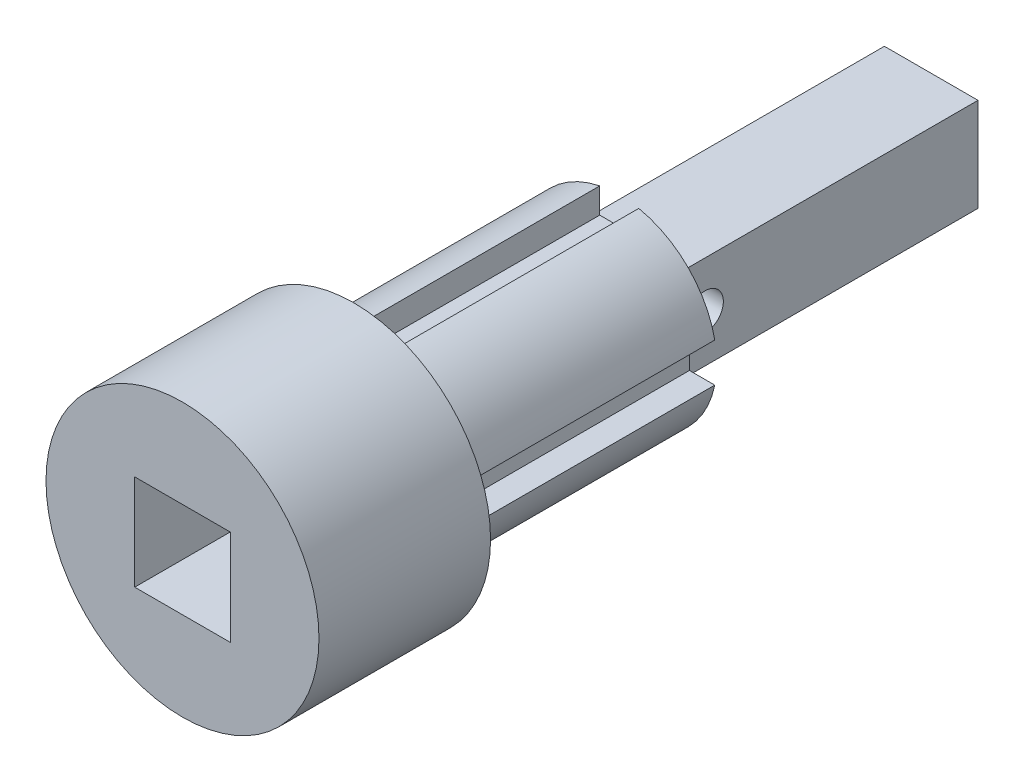
SolidWorks part; units mm, degrees
ref_plane "Plano frontal" through (0, 0, 0) normal (0, 0, 1) x (1, 0, 0)
ref_plane "Plano superior" through (0, 0, 0) normal (0, 1, 0) x (1, 0, 0)
ref_plane "Plano direito" through (0, 0, 0) normal (1, 0, 0) x (0, 0, -1)
sketch "Esboço1" plane through (0, 0, 0) normal (0, 0, 1) x (1, 0, 0)
  circle A0 centre (0, 0) radius 17.5
  dimension "D1" = 35
extrude "Ressalto-extrusão1" add sketch "Esboço1" along normal blind 22
sketch "Esboço2" plane through (0, 0, 0) normal (0, 0, -1) x (-1, 0, 0)
  line L3 (-6.125, 6.125) -> (6.125, 6.125)
  line L4 (-6.125, 6.125) -> (-6.125, -6.125)
  line L5 (-6.125, -6.125) -> (6.125, -6.125)
  line L6 (6.125, 6.125) -> (6.125, -6.125)
  point P5 (0, 0)
  dimension "D1" = 12.25
  dimension "D2" = 12.25
extrude "Corte-extrusão1" cut sketch "Esboço2" against normal blind 25
sketch "Esboço3" plane through (0, 0, 0) normal (0, 0, -1) x (-1, 0, 0)
  circle A0 centre (0, 0) radius 12.5
  dimension "D1" = 25
extrude "Ressalto-extrusão2" add sketch "Esboço3" along normal blind 34
sketch "Esboço4" plane through (0, 0, -34) normal (0, 0, -1) x (-1, 0, 0)
  line L2 (-2.5, -9) -> (2.5, -9)
  line L3 (-2.5, 15) -> (2.5, 15)
  line L4 (-2.5, 15) -> (-2.5, 9)
  line L5 (-2.5, 9) -> (2.5, 9)
  line L6 (2.5, 15) -> (2.5, 9)
  line L7 (9, 2.5) -> (15, 2.5)
  line L8 (9, 2.5) -> (9, -2.5)
  line L9 (9, -2.5) -> (15, -2.5)
  line L10 (15, 2.5) -> (15, -2.5)
  line L11 (-2.5, -15) -> (2.5, -15)
  line L12 (2.5, -15) -> (2.5, -9)
  line L13 (-2.5, -15) -> (-2.5, -9)
  line L14 (-15, 2.5) -> (-15, -2.5)
  line L15 (-9, -2.5) -> (-15, -2.5)
  line L16 (-9, 2.5) -> (-9, -2.5)
  line L17 (-9, 2.5) -> (-15, 2.5)
  dimension "D1" = 5
  dimension "D2" = 5
  dimension "D3" = 6
  dimension "D6" = 6
extrude "Corte-extrusão2" cut sketch "Esboço4" against normal blind 32
fillet "Filete2" radius 2 3 edges at (10.6237, 2.5, -2) (10.6237, -2.5, -2) (9, 0, -2)
fillet "Filete3" radius 2 3 edges at (-2.5, -10.6237, -2) (2.5, -10.6237, -2) (0, -9, -2)
fillet "Filete4" radius 2 3 edges at (-10.6237, 2.5, -2) (-9, 0, -2) (-10.6237, -2.5, -2)
fillet "Filete5" radius 2 3 edges at (-2.5, 10.6237, -2) (2.5, 10.6237, -2) (0, 9, -2)
sketch "Esboço5" plane through (0, 0, -34) normal (0, 0, -1) x (-1, 0, 0)
  line L1 (6, 6) -> (-6, 6)
  line L2 (6, 6) -> (6, -6)
  line L3 (6, -6) -> (-6, -6)
  line L4 (-6, 6) -> (-6, -6)
  line L5 (6, 6) -> (-6, -6) construction
  line L6 (6, -6) -> (-6, 6) construction
  point P0 (0, 0)
  dimension "D1" = 12
  dimension "D2" = 12
extrude "Ressalto-extrusão3" add sketch "Esboço5" along normal blind 40
sketch "Esboço6" plane through (6, 0, 0) normal (1, 0, 0) x (0, 0, -1)
  circle A0 centre (39, 0) radius 2.35
extrude "Corte-extrusão3" cut sketch "Esboço6" against normal blind 15 and the other way blind 14
